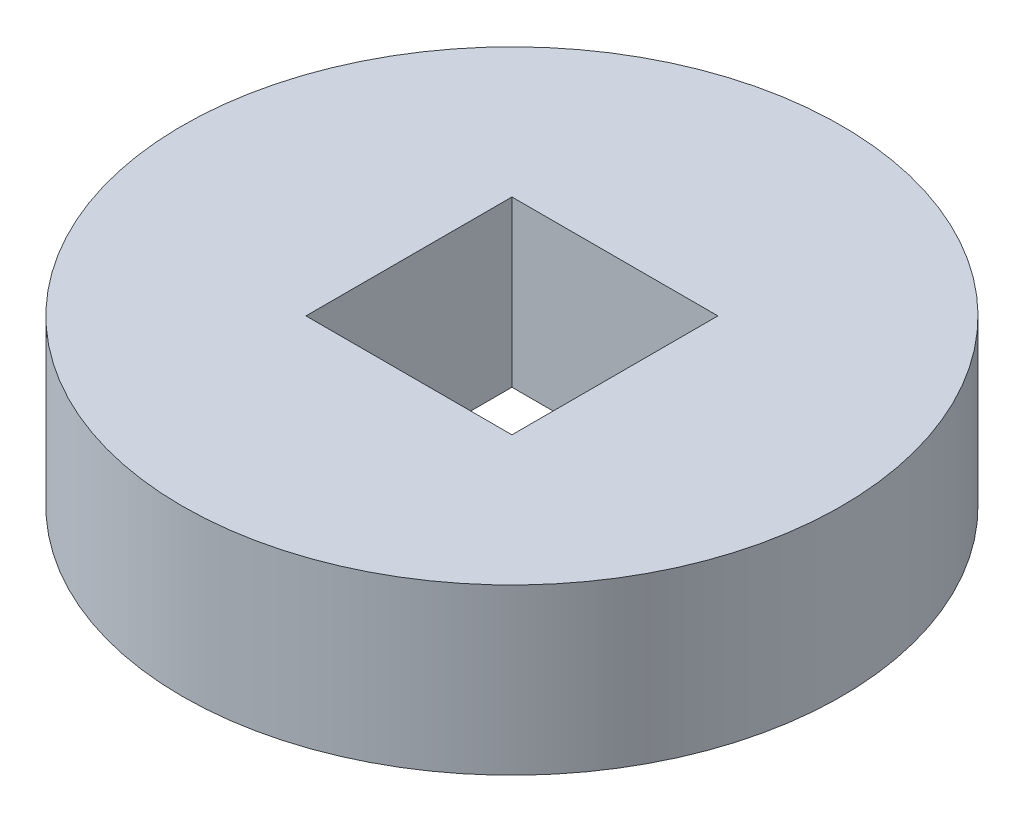
SolidWorks part; units mm, degrees
ref_plane "Front Plane" through (0, 0, 0) normal (0, 0, 1) x (1, 0, 0)
ref_plane "Top Plane" through (0, 0, 0) normal (0, 1, 0) x (1, 0, 0)
ref_plane "Right Plane" through (0, 0, 0) normal (1, 0, 0) x (0, 0, -1)
sketch "Sketch1" plane through (0, 0, 0) normal (0, 1, 0) x (1, 0, 0)
  line L1 (-12.5, -12.5) -> (12.5, -12.5)
  line L2 (-12.5, -12.5) -> (-12.5, 12.5)
  line L3 (-12.5, 12.5) -> (12.5, 12.5)
  line L4 (12.5, -12.5) -> (12.5, 12.5)
  line L5 (-12.5, -12.5) -> (12.5, 12.5) construction
  line L6 (-12.5, 12.5) -> (12.5, -12.5) construction
  circle A1 centre (0, 0) radius 40
  dimension "D1" = 25
  dimension "D2" = 80
  dimension "D3" = 25
extrude "Boss-Extrude1" add sketch "Sketch1" along normal blind 20
